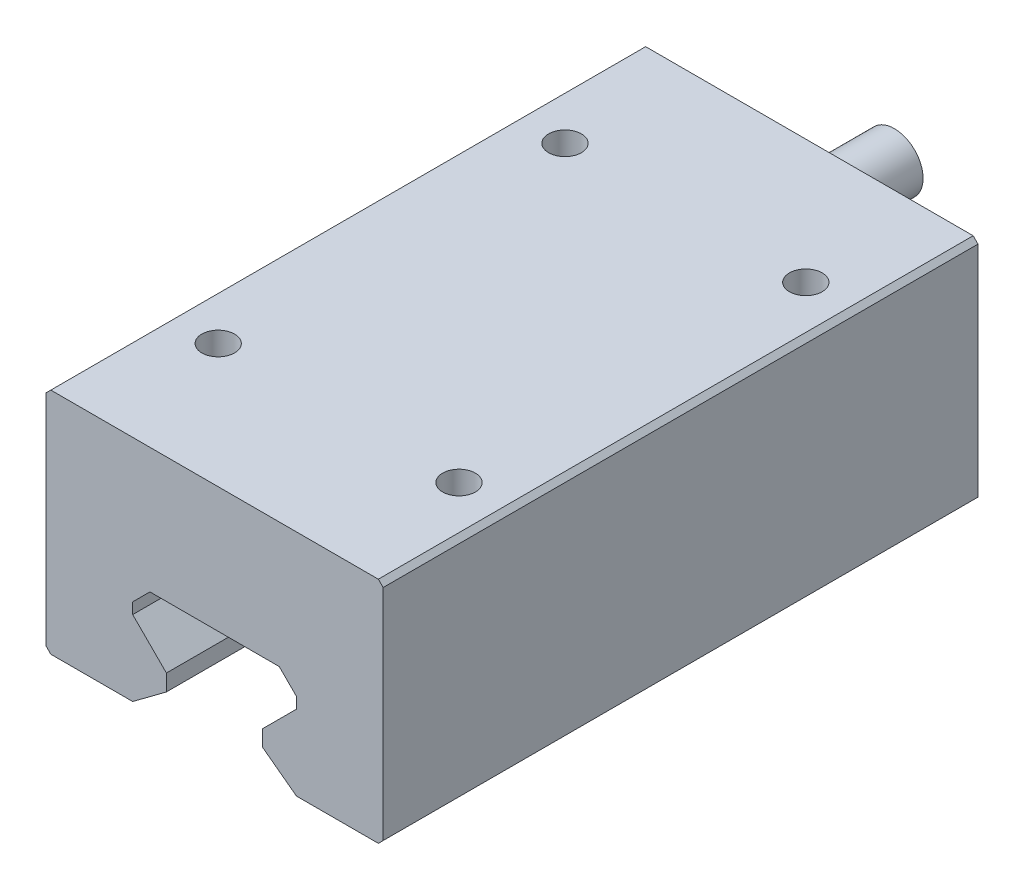
SolidWorks part; units mm, degrees
ref_plane "前基準面" through (0, 0, 0) normal (0, 0, 1) x (1, 0, 0)
ref_plane "上基準面" through (0, 0, 0) normal (0, 1, 0) x (1, 0, 0)
ref_plane "右基準面" through (0, 0, 0) normal (1, 0, 0) x (0, 0, -1)
sketch "草圖2" plane through (0, 0, 0) normal (0, 0, 1) x (1, 0, 0)
  line L0 (17, 0) -> (-17, 0) construction
  line L1 (-17, 0) -> (-17, 7.5) construction
  line L2 (-17, 7.5) -> (-10, 12.7214) construction
  line L3 (-10, 12.7214) -> (-10, 16.1299) construction
  line L4 (-10, 16.1299) -> (-17, 23.1299) construction
  line L5 (-17, 23.1299) -> (-17, 25.4259) construction
  line L6 (-17, 25.4259) -> (-13.4259, 29) construction
  line L7 (-13.4259, 29) -> (13.4259, 29) construction
  line L8 (0, 29) -> (0, 0) construction
  line L9 (17, 25.4259) -> (13.4259, 29) construction
  line L10 (17, 23.1299) -> (17, 25.4259) construction
  line L11 (10, 16.1299) -> (17, 23.1299) construction
  line L12 (10, 12.7214) -> (10, 16.1299) construction
  line L13 (17, 7.5) -> (10, 12.7214) construction
  line L14 (17, 0) -> (17, 7.5) construction
  line L15 (-17, 7.5) -> (-35, 7.5)
  line L16 (-35, 7.5) -> (-35, 55)
  line L17 (-35, 55) -> (35, 55)
  line L18 (35, 55) -> (35, 7.5)
  line L19 (35, 7.5) -> (17, 7.5)
  line L20 (17, 7.5) -> (10, 12.7214)
  line L21 (10, 12.7214) -> (10, 16.1299)
  line L22 (10, 16.1299) -> (17, 23.1299)
  line L23 (17, 23.1299) -> (17, 25.4259)
  line L24 (17, 25.4259) -> (13.4259, 29)
  line L25 (13.4259, 29) -> (-13.4259, 29)
  line L26 (-13.4259, 29) -> (-17, 25.4259)
  line L27 (-17, 25.4259) -> (-17, 23.1299)
  line L28 (-17, 23.1299) -> (-10, 16.1299)
  line L29 (-10, 16.1299) -> (-10, 12.7214)
  line L30 (-10, 12.7214) -> (-17, 7.5)
  dimension "D1" = 17
  dimension "D2" = 7.5
  dimension "D3" = 29
  dimension "D4" = 135
  dimension "D5" = 135
  dimension "D6" = 10
  dimension "D7" = 70
  dimension "D8" = 55
extrude "伸長1" add sketch "草圖2" along normal blind 123.5
chamfer "導角1" distance 1 angle 45 4 edges at (-35, 55, 61.75) (-35, 7.5, 61.75) (35, 7.5, 61.75) (35, 55, 61.75)
hole_wizard "M8 螺紋孔1" positions "草圖4" profile "草圖3" tap size "M8" standard "GB"
sketch "草圖4" plane through (0, 55, 0) normal (0, 1, 0) x (-1, 0, 0)
  line L1 (25, 25.75) -> (-25, 25.75)
  line L2 (25, 25.75) -> (25, 97.75)
  line L3 (25, 97.75) -> (-25, 97.75)
  line L4 (-25, 25.75) -> (-25, 97.75)
  line L5 (0, 0) -> (0, 25.75) construction
  line L7 (25, 61.75) -> (34, 61.75) construction
  line L8 (34, 0) -> (34, 123.5) construction
  point P0 (25, 97.75)
  point P127 (25, 25.75)
  point P129 (-25, 25.75)
  point P131 (-25, 97.75)
  dimension "D1" = 50
  dimension "D2" = 72
sketch "草圖3" plane through (-25, 55, 97.75) normal (1, 0, 0) x (0, 0, 1)
  line L0 (0, 0) -> (0, 17.0429)
  line L1 (0, 17.0429) -> (3.4, 15)
  line L2 (3.4, 15) -> (3.4, 0)
  line L5 (3.4, 0) -> (0, 0)
  line L10 (0, 17.0429) -> (-3.4, 15) construction
  line L11 (0, -6.35) -> (0, 107.95) construction
  dimension "螺孔鑽直徑" = 6.8
  dimension "螺孔鑽深度" = 15
  dimension "導頭角度" = 118
cosmetic thread "鑽孔螺紋1" parameters "D1"=12, "D2"=8
cosmetic thread "鑽孔螺紋2" parameters "D1"=12, "D2"=8
cosmetic thread "鑽孔螺紋3" parameters "D1"=12, "D2"=8
cosmetic thread "鑽孔螺紋4" parameters "D1"=12, "D2"=8
sketch "草圖5" plane through (0, 0, 0) normal (0, 0, -1) x (-1, 0, 0)
  circle A0 centre (-2.0376, 44.5185) radius 5.9615
extrude "伸長2" add sketch "草圖5" along normal blind 15.6
